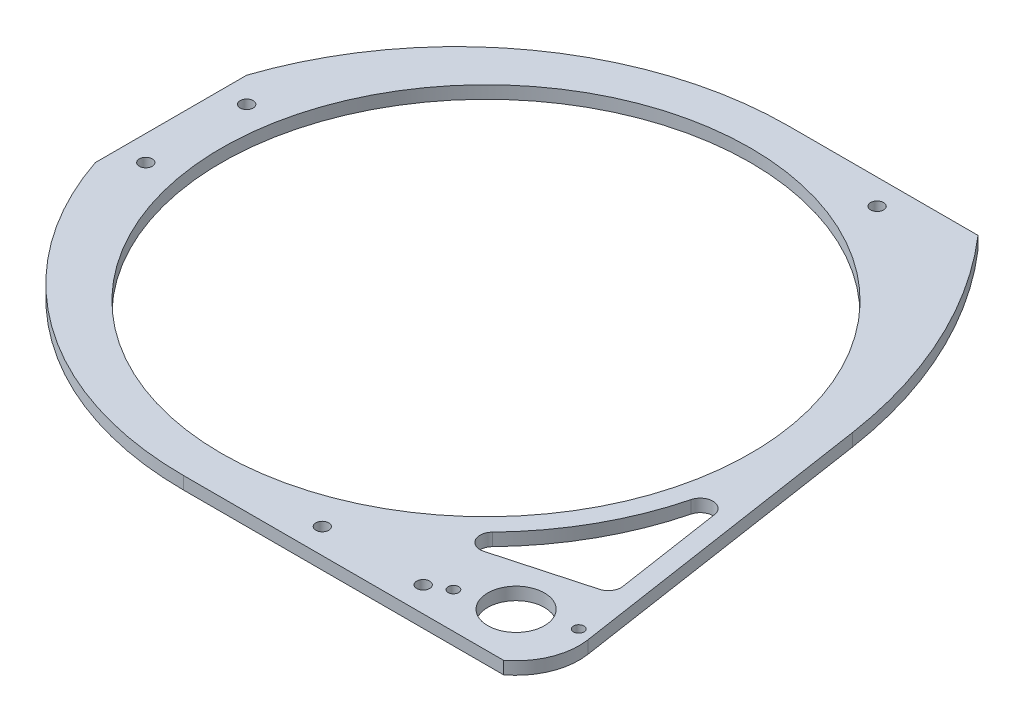
SolidWorks part; units mm, degrees
material "3003 Alloy"
ref_plane "Front Plane" through (0, 0, 0) normal (0, 0, 1) x (1, 0, 0)
ref_plane "Top Plane" through (0, 0, 0) normal (0, 1, 0) x (1, 0, 0)
ref_plane "Right Plane" through (0, 0, 0) normal (1, 0, 0) x (0, 0, -1)
sketch "Sketch1" plane through (0, 0, 0) normal (0, 1, 0) x (1, 0, 0)
  line L0 (-145.923, 0) -> (69.977, 0) construction
  line L1 (0, 152.4) -> (95.377, 152.4)
  line L2 (-158.623, 38.1) -> (-158.623, -38.1)
  line L3 (0, -152.4) -> (95.377, -152.4)
  line L4 (152.4, 152.4) -> (152.4, -86.7552) construction
  line L5 (-133.223, -12.7) -> (-158.623, -12.7) construction
  line L6 (-133.223, -12.7) -> (-133.223, 12.7) construction
  line L7 (-133.223, 12.7) -> (-158.623, 12.7) construction
  line L8 (-158.623, -12.7) -> (-158.623, 12.7)
  line L9 (-133.223, -12.7) -> (-158.623, 12.7) construction
  line L10 (-133.223, 12.7) -> (-158.623, -12.7) construction
  line L11 (69.977, 0) -> (69.977, -127) construction
  line L12 (69.977, 0) -> (69.977, 127) construction
  line L13 (69.977, -127) -> (95.377, -127) construction
  line L14 (69.977, -127) -> (69.977, -152.4) construction
  line L15 (69.977, -152.4) -> (95.377, -152.4) construction
  line L16 (95.377, -127) -> (95.377, -152.4) construction
  line L17 (0, -1000) -> (0, 49000) construction
  line L18 (69.977, 127) -> (95.377, 127) construction
  line L19 (69.977, 127) -> (69.977, 152.4) construction
  line L20 (69.977, 152.4) -> (95.377, 152.4) construction
  line L21 (95.377, 127) -> (95.377, 152.4) construction
  line L22 (-145.923, 0) -> (-145.923, 25.4) construction
  line L23 (-145.923, 0) -> (-145.923, -25.4) construction
  line L24 (69.977, -152.4) -> (95.377, -127) construction
  line L25 (95.377, -152.4) -> (69.977, -127) construction
  line L26 (69.977, 127) -> (95.377, 152.4) construction
  line L27 (95.377, 127) -> (69.977, 152.4) construction
  line L28 (0, 0) -> (142.1573, -127) construction
  line L29 (88.8171, -142.7547) -> (76.1606, -146.493) construction
  line L30 (-904.623, -152.4) -> (49095.377, -152.4) construction
  line L31 (124.179, -110.9386) -> (24016.4727, 43811.246) construction
  line L32 (142.1573, -127) -> (134.9623, -102.6403) construction
  line L33 (117.7976, -134.1949) -> (134.9623, -102.6403) construction
  line L34 (142.1573, -152.4) -> (95.377, -152.4)
  line L35 (142.1573, -152.4) -> (161.2073, -152.4)
  line L36 (147.5933, 49.2265) -> (-7335.7334, 49486.053) construction
  line L37 (173.5496, -122.2481) -> (149.785, 34.7472)
  line L38 (82.677, -139.7) -> (108.077, -139.7) construction
  circle A0 centre (0, 0) radius 127 construction
  circle A1 centre (0, 0) radius 133.223
  arc A2 (-158.623, 38.1) -> (0, 152.4) centre (0, -14.8167) cw
  arc A3 (-158.623, -38.1) -> (0, -152.4) centre (0, 14.8167) ccw
  circle A4 centre (-145.923, 25.4) radius 3.2639
  circle A5 centre (-145.923, -25.4) radius 3.2639
  circle A6 centre (57.277, 139.7) radius 3.2639
  circle A7 centre (57.277, -139.7) radius 3.2639
  arc A8 (95.377, 152.4) -> (95.377, -152.4) centre (-79.7641, 0) cw construction
  circle A9 centre (142.1573, -127) radius 25.4 construction
  circle A10 centre (117.7976, -134.1949) radius 2.6289
  circle A11 centre (166.5169, -119.8051) radius 2.6289
  circle A12 centre (142.1573, -127) radius 14.2875
  arc A13 (161.2073, -152.4) -> (172.6068, -118.0063) centre (142.1573, -127) ccw
  arc A14 (95.377, 152.4) -> (149.785, 34.7472) centre (-79.7641, 0) cw
  circle A15 centre (108.077, -139.7) radius 3.2639
  point P4 (-145.923, 0)
  point P24 (-158.623, 38.1)
  point P31 (-158.623, -38.1)
  point P38 (82.677, 139.7)
  point P41 (82.677, -139.7)
  point P55 (124.179, -110.9386)
  point P58 (142.1573, -152.4)
  point P64 (173.5496, -122.2481)
  dimension "D1" = 254
  dimension "D12" = 152.4
  dimension "D15" = 25.4
  dimension "D16" = 6.5278
  dimension "D18" = 6.5278
  dimension "D21" = 6.5278
  dimension "D24" = 6.5278
  dimension "D26" = 50.8
  dimension "D27" = 5.2578
  dimension "D28" = 5.2578
  dimension "D29" = 28.575
  dimension "D30" = 63.5
  dimension "D32" = 6.5278
  dimension "D3" = 25.4
  dimension "D4" = 25.4
  dimension "D5" = 25.4
  dimension "D6" = 215.9
  dimension "D7" = 127
  dimension "D8" = 25.4
  dimension "D9" = 25.4
  dimension "D10" = 127
  dimension "D11" = 25.4
  dimension "D13" = 25.4
  dimension "D14" = 25.4
  dimension "D17" = 25.4
  dimension "D19" = 12.7
  dimension "D20" = 25.4
  dimension "D22" = 12.7
  dimension "D23" = 25.4
  dimension "D25" = 190.6245
  dimension "D31" = 25.4
  dimension "D2" = 6.223
extrude "Boss-Extrude1" add sketch "Sketch1" along normal blind 6.35 contours A8 L1 A2 L2 A3 L3 A7 A6 A5 A4 A1
sketch "Sketch2" plane through (0, 6.35, 0) normal (0, 1, 0) x (1, 0, 0)
  line L0 (0, -152.4) -> (161.2073, -152.4) construction
  line L1 (69.977, -152.4) -> (95.377, -152.4) construction
  line L2 (69.977, -152.4) -> (69.977, -127) construction
  line L3 (69.977, -127) -> (95.377, -127) construction
  line L4 (95.377, -152.4) -> (95.377, -127) construction
  line L11 (81.0963, -117.475) -> (159.9072, -95.764)
  line L13 (142.748, 0) -> (142.748, 17.5942)
  line L14 (173.5496, -122.2481) -> (149.785, 34.7472) construction
  line L15 (142.748, 17.5942) -> (159.9072, -95.764)
  line L16 (142.748, 0) -> (0, 0) construction
  circle A0 centre (57.277, -139.7) radius 3.2639 construction
  circle A1 centre (57.277, -139.7) radius 3.2639 construction
  arc A2 (81.0963, -117.475) -> (142.748, 0) centre (0, 0) ccw
  circle A3 centre (0, 0) radius 133.223 construction
  circle A5 centre (142.1573, -127) radius 14.2875 construction
  dimension "D4" = 9.525
  dimension "D6" = 9.525
  dimension "D1" = 25.4
  dimension "D2" = 25.4
  dimension "D3" = 12.7
  dimension "D5" = 25.4
  dimension "D7" = 9.525
extrude "Cut-Extrude1" cut sketch "Sketch2" against normal blind 6.35
fillet "Fillet1" radius 6.35 3 edges at (81.0963, 3.175, 117.475) (142.748, 3.175, -17.5942) (159.9072, 3.175, 95.764)
